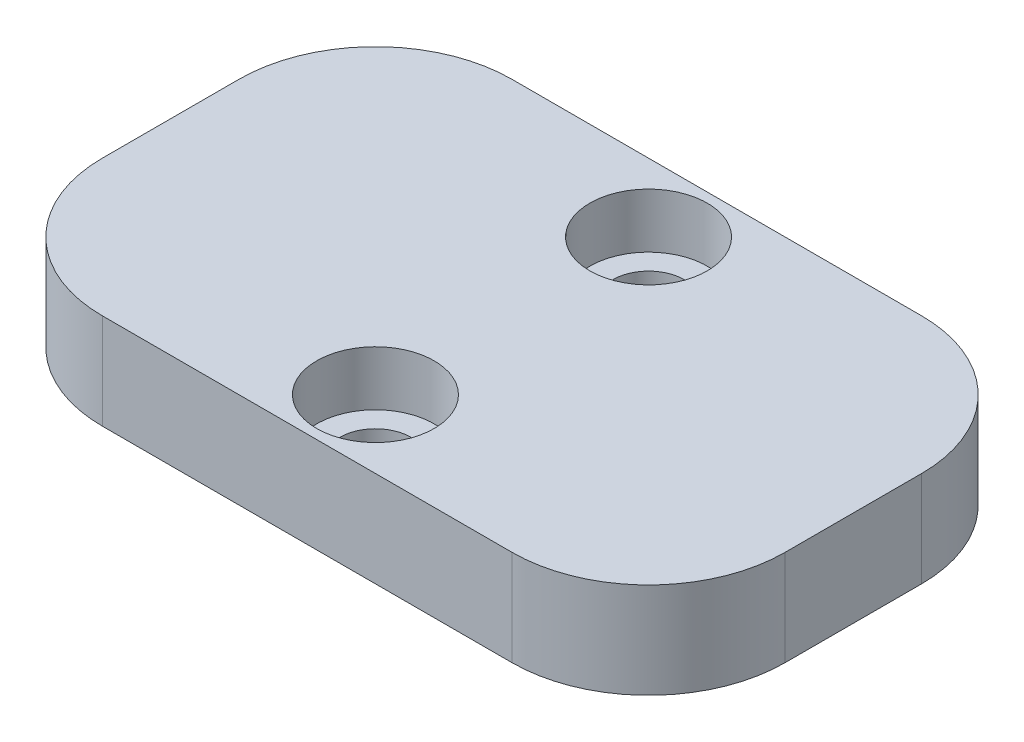
SolidWorks part; units mm, degrees
ref_plane "Front Plane" through (0, 0, 0) normal (0, 0, 1) x (1, 0, 0)
ref_plane "Top Plane" through (0, 0, 0) normal (0, 1, 0) x (1, 0, 0)
ref_plane "Right Plane" through (0, 0, 0) normal (1, 0, 0) x (0, 0, -1)
sketch "Sketch1" plane through (0, 0, 0) normal (0, 1, 0) x (1, 0, 0)
  line L0 (25, 30) -> (25, 0) construction
  line L1 (0, 0) -> (50, 0)
  line L2 (0, 0) -> (0, 30)
  line L3 (0, 30) -> (50, 30)
  line L4 (50, 0) -> (50, 30)
  line L5 (0, 15) -> (50, 15) construction
  circle A0 centre (25, 25) radius 2.6
  circle A1 centre (25, 5) radius 2.6
  dimension "D3" = 10
  dimension "D4" = 5.2
  dimension "D5" = 5.2
  dimension "D1" = 50
  dimension "D2" = 30
  dimension "D6" = 10
extrude "Boss-Extrude1" add sketch "Sketch1" along normal blind 7
fillet "Fillet1" radius 10 4 edges at (50, 3.5, -30) (0, 3.5, -30) (0, 3.5, 0) (50, 3.5, 0)
sketch "Sketch2" plane through (0, 7, 0) normal (0, 1, 0) x (1, 0, 0)
  circle A0 centre (25, 25) radius 4.3
  circle A1 centre (25, 5) radius 4.3
  dimension "D1" = 8.6
extrude "Cut-Extrude1" cut sketch "Sketch2" against normal blind 4
